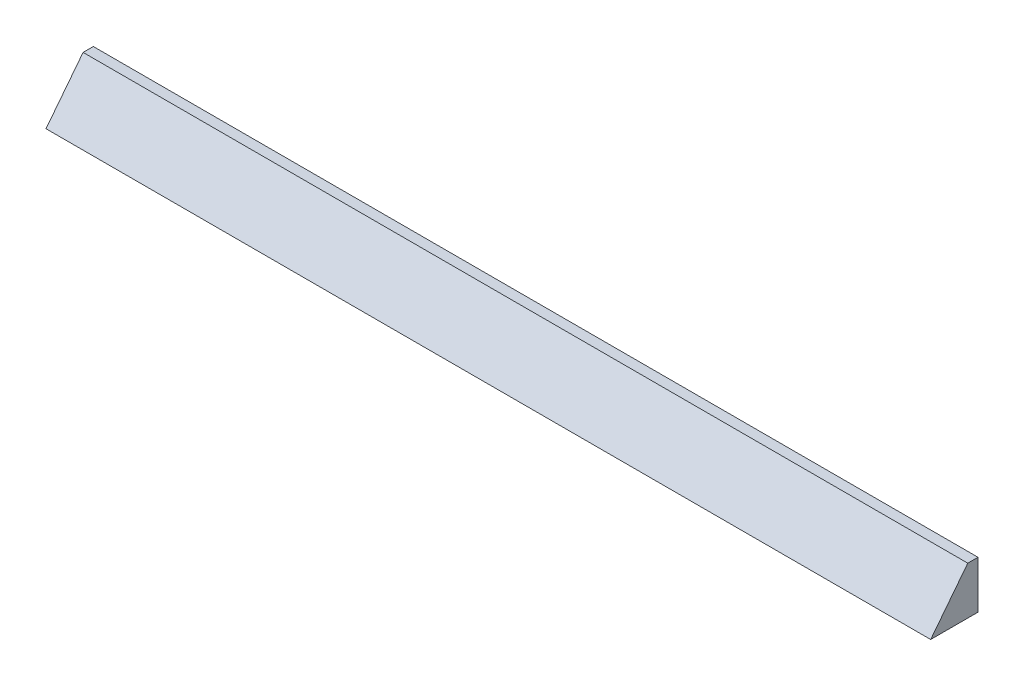
SolidWorks part; units mm, degrees
ref_plane "Plano frontal" through (0, 0, 0) normal (0, 0, 1) x (1, 0, 0)
ref_plane "Plano superior" through (0, 0, 0) normal (0, 1, 0) x (1, 0, 0)
ref_plane "Plano direito" through (0, 0, 0) normal (1, 0, 0) x (0, 0, -1)
sketch "Esboço59" plane through (55.1891, 0, 0) normal (-1, 0, 0) x (0, 0, 1)
  line L0 (38, 1.3305) -> (38, -3.6695)
  line L1 (38, -3.6695) -> (42.9742, -3.6695)
  line L2 (42.9742, -3.6695) -> (39.0751, 1.3305)
  line L3 (39.0751, 1.3305) -> (38, 1.3305)
  arc A0 (17.5, -49.5145) -> (17.5, 10.4855) centre (17.5, -19.5145) ccw construction
extrude "Ressalto-extrusão15" add sketch "Esboço59" along normal blind 93 separate body
